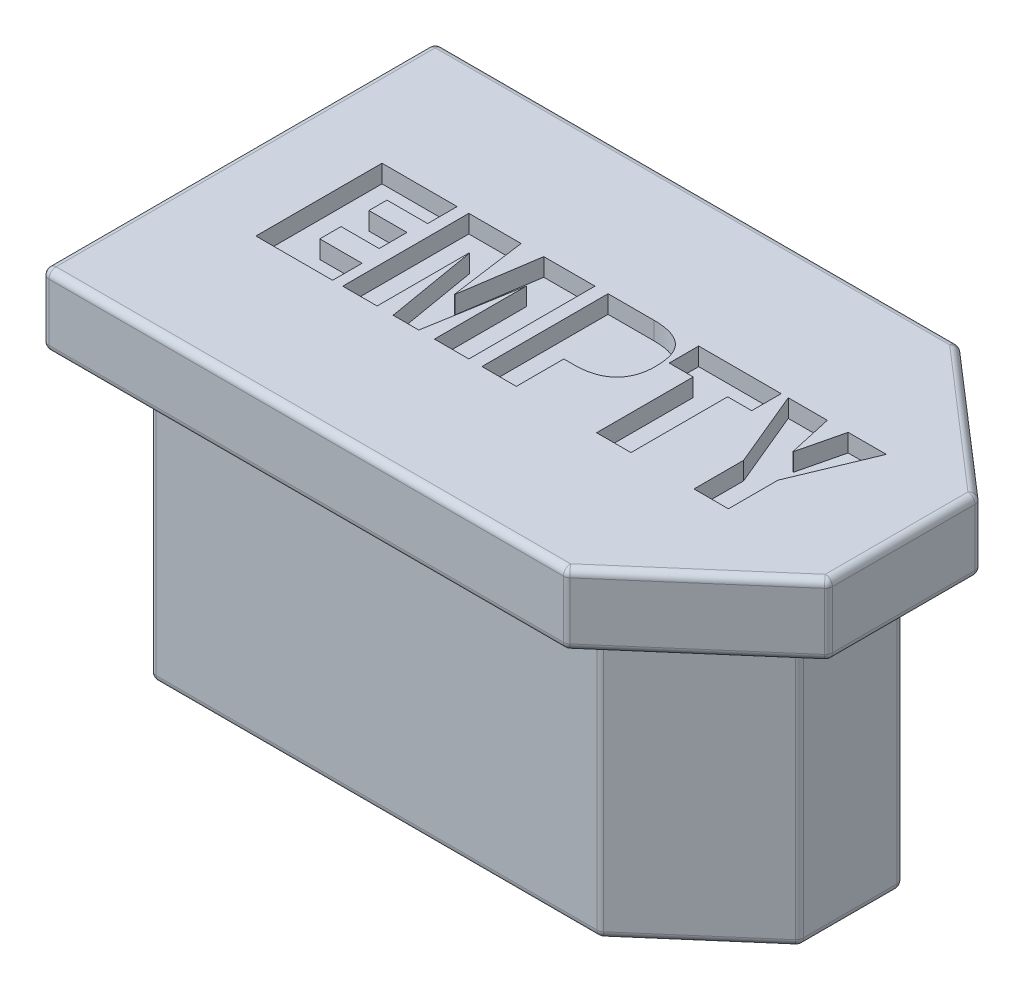
SolidWorks part; units mm, degrees
ref_plane "Front Plane" through (0, 0, 0) normal (0, 0, 1) x (1, 0, 0)
ref_plane "Top Plane" through (0, 0, 0) normal (0, 1, 0) x (1, 0, 0)
ref_plane "Right Plane" through (0, 0, 0) normal (1, 0, 0) x (0, 0, -1)
sketch "Sketch1" plane through (0, 0, 0) normal (0, 1, 0) x (1, 0, 0)
  line L0 (-7.8002, 4) -> (4.7998, 4)
  line L1 (4.7998, 4) -> (7.8002, 1.4)
  line L2 (7.8002, 1.4) -> (7.8002, -1.4)
  line L3 (7.8002, -1.4) -> (4.7998, -4)
  line L4 (4.7998, -4) -> (-7.8002, -4)
  line L5 (-7.8002, -4) -> (-7.8002, 4)
  line L6 (-7.8002, 0) -> (7.8002, 0) construction
  dimension "D1" = 8
  dimension "D2" = 12.6
  dimension "D3" = 139.09
  dimension "D4" = 2.8
extrude "Boss-Extrude1" add sketch "Sketch1" along normal mid plane 8
shell "Shell1" thickness 0.8
sketch "Sketch2" plane through (0, 4, 0) normal (0, 1, 0) x (1, 0, 0)
  line L0 (-7.8002, 4) -> (-7.8002, -4) construction
  line L1 (4.7998, 4) -> (-7.8002, 4) construction
  line L2 (7.8002, 1.4) -> (4.7998, 4) construction
  line L3 (7.8002, -1.4) -> (7.8002, 1.4) construction
  line L4 (4.7998, -4) -> (7.8002, -1.4) construction
  line L5 (-7.8002, -4) -> (4.7998, -4) construction
  line L6 (-7.8002, 4) -> (-7.8002, -4) construction
  line L7 (4.7998, 4) -> (-7.8002, 4) construction
  line L8 (7.8002, 1.4) -> (4.7998, 4) construction
  line L9 (7.8002, -1.4) -> (7.8002, 1.4) construction
  line L10 (4.7998, -4) -> (7.8002, -1.4) construction
  line L11 (-7.8002, -4) -> (4.7998, -4) construction
  line L12 (-9.3002, 5.5) -> (-9.3002, -5.5)
  line L13 (-9.3002, -5.5) -> (5.3593, -5.5)
  line L14 (5.3593, -5.5) -> (9.3002, -2.085)
  line L15 (9.3002, -2.085) -> (9.3002, 2.085)
  line L16 (9.3002, 2.085) -> (5.3593, 5.5)
  line L17 (5.3593, 5.5) -> (-9.3002, 5.5)
  dimension "D1" = 1.5
extrude "Boss-Extrude2" add sketch "Sketch2" along normal blind 2
sketch "Sketch4" plane through (0, -4, 0) normal (0, -1, 0) x (1, 0, 0)
  line L0 (-1.0002, -3.2) -> (-1.0002, -2)
  line L3 (4.5014, -3.2) -> (-7.0002, -3.2) construction
  line L5 (-1.0002, -2) -> (0.9998, -2)
  line L6 (0.9998, -2) -> (0.9998, -3.2)
  line L7 (-1.0002, -3.2) -> (0.9998, -3.2)
  dimension "D1" = 1.2
  dimension "D2" = 2
  dimension "D3" = 6
extrude "Boss-Extrude4" add sketch "Sketch4" against normal up to next
sketch "Sketch5" plane through (0, 4, 0) normal (0, -1, 0) x (1, 0, 0)
  line L0 (-0.5502, -2) -> (-0.5502, 2)
  line L1 (0.9998, -2) -> (-1.0002, -2) construction
  line L2 (-0.5502, 2) -> (0.5498, 2)
  line L3 (0.5498, 2) -> (0.5498, -2)
  line L4 (0.9998, -2) -> (-1.0002, -2) construction
  line L5 (0.5498, -2) -> (-0.5502, -2)
  line L6 (-0.0002, -2) -> (-0.0002, 2) construction
  dimension "D1" = 4
  dimension "D2" = 1.1
extrude "Cut-Extrude1" cut sketch "Sketch5" against normal blind 1
fillet "Fillet1" radius 0.2 78 edges at (4.5014, 0, -3.2) (7.0002, 0, -1.0347) (7.0002, 0, 1.0347) (4.5014, 0, 3.2) (-7.0002, 0, -3.2) (-1.0002, 0, -3.2) (-1.0002, 0, -2) (0.9998, 0, -2) (0.9998, 0, -3.2) (-7.0002, 0, 3.2) (0.9998, 4, -2.6) (0.9998, -4, -2.6) (2.7506, -4, -3.2) (-1.0002, 4, -2.6) (-1.0002, -4, -2.6) (-0.0002, 4, 2) (5.7508, -4, -2.1173) (-4.0002, -4, -3.2) (-0.0002, -4, -2) (-0.0002, 5, 2) (0.5498, 4.5, 2) (-0.5502, 4.5, 2) (0.5498, 5, 0) (-0.5502, 5, 0) (5.7508, 4, -2.1173) (2.7506, 4, -3.2) (-0.0002, 5, -2) (-4.0002, 4, -3.2) (7.0002, -4, 0) (7.0002, 4, 0) (-1.2494, -4, 3.2) (-1.2494, 4, 3.2) (5.7508, -4, 2.1173) (5.7508, 4, 2.1173) (-7.0002, -4, 0) (-7.0002, 4, 0) (-1.9705, 4, -5.5) (-9.3002, 4, 0) (-1.9705, 4, 5.5) (7.3297, 4, 3.7925) (9.3002, 4, 0) (7.3297, 4, -3.7925) (-1.9705, 6, -5.5) (-9.3002, 6, 0) (-1.9705, 6, 5.5) (7.3297, 6, 3.7925) (9.3002, 6, 0) (7.3297, 6, -3.7925) (5.3593, 5, -5.5) (9.3002, 5, -2.085) (9.3002, 5, 2.085) (5.3593, 5, 5.5) (-9.3002, 5, 5.5) (-9.3002, 5, -5.5) (-7.8002, -4, 0) (6.3, -4, 2.7) (7.8002, -4, 0) (6.3, -4, -2.7) (-1.5002, -4, -4) (-7.8002, 4, 0) (-1.5002, 4, 4) (6.3, 4, 2.7) (7.8002, 4, 0) (6.3, 4, -2.7) (-1.5002, 4, -4) (-7.8002, 0, -4) (4.7998, 0, -4) (7.8002, 0, -1.4) (7.8002, 0, 1.4) (4.7998, 0, 4) (-7.8002, 0, 4) (-1.5002, -4, 4)
sketch "Sketch6" plane through (0, 6, 0) normal (0, 1, 0) x (1, 0, 0)
  line L0 (-7.0504, 1.7632) -> (-4.9509, 1.7632)
  line L1 (-4.9509, 1.7632) -> (-4.9509, 0.9388)
  line L2 (-4.9509, 0.9388) -> (-6.0886, 0.9388)
  line L3 (-6.0886, 0.9388) -> (-6.0886, 0.4351)
  line L4 (-6.0886, 0.4351) -> (-5.0253, 0.4351)
  line L5 (-5.0253, 0.4351) -> (-5.0253, -0.3435)
  line L6 (-5.0253, -0.3435) -> (-6.0886, -0.3435)
  line L7 (-6.0886, -0.3435) -> (-6.0886, -0.9388)
  line L8 (-6.0886, -0.9388) -> (-4.9065, -0.9388)
  line L9 (-4.9065, -0.9388) -> (-4.9065, -1.7632)
  line L10 (-4.9065, -1.7632) -> (-7.0504, -1.7632)
  line L11 (-7.0504, -1.7632) -> (-7.0504, 1.7632)
  line L12 (-4.6231, 1.7632) -> (-3.1619, 1.7632)
  line L13 (-3.1619, 1.7632) -> (-2.8649, -0.3893)
  line L14 (-2.8649, -0.3893) -> (-2.8549, -0.3893)
  line L15 (-2.8549, -0.3893) -> (-2.5272, 1.7632)
  line L16 (-2.5272, 1.7632) -> (-1.0968, 1.7632)
  line L17 (-1.0968, 1.7632) -> (-1.0968, -1.7632)
  line L18 (-1.0968, -1.7632) -> (-2.0585, -1.7632)
  line L19 (-2.0585, -1.7632) -> (-2.0585, 0.8086)
  line L20 (-2.0585, 0.8086) -> (-2.4964, -1.7632)
  line L21 (-2.4964, -1.7632) -> (-3.2134, -1.7632)
  line L22 (-3.2134, -1.7632) -> (-3.6514, 0.8086)
  line L23 (-3.6514, 0.8086) -> (-3.6614, 0.8086)
  line L24 (-3.6614, 0.8086) -> (-3.6614, -1.7632)
  line L25 (-3.6614, -1.7632) -> (-4.6231, -1.7632)
  line L26 (-4.6231, -1.7632) -> (-4.6231, 1.7632)
  line L27 (-0.7304, 1.7632) -> (0.5527, 1.7632)
  line L28 (0.5333, -0.4351) -> (0.2314, -0.4351)
  line L29 (0.2314, -0.4351) -> (0.2314, -1.7632)
  line L30 (0.2314, -1.7632) -> (-0.7304, -1.7632)
  line L31 (-0.7304, 1.7632) -> (-0.7304, -1.7632)
  line L32 (-7.0504, 0) -> (7.0504, 0) construction
  line L34 (0, 0) -> (0, 1.7632) construction
  line L35 (1.8028, 1.7632) -> (4.1098, 1.7632)
  line L36 (4.1098, 1.7632) -> (4.1098, 0.9388)
  line L37 (4.1098, 0.9388) -> (3.4371, 0.9388)
  line L38 (3.4371, 0.9388) -> (3.4371, -1.7632)
  line L39 (3.4371, -1.7632) -> (2.4754, -1.7632)
  line L40 (2.4754, -1.7632) -> (2.4754, 0.9388)
  line L41 (2.4754, 0.9388) -> (1.8028, 0.9388)
  line L42 (1.8028, 0.9388) -> (1.8028, 1.7632)
  line L43 (5.982, 1.7632) -> (7.0504, 1.7632)
  line L44 (7.0504, 1.7632) -> (6.1602, -0.3757)
  line L45 (6.1602, -0.3757) -> (6.1602, -1.7632)
  line L46 (6.1602, -1.7632) -> (5.1984, -1.7632)
  line L47 (5.1984, -1.7632) -> (5.1984, -0.3757)
  line L48 (5.1984, -0.3757) -> (4.3083, 1.7632)
  line L49 (4.3083, 1.7632) -> (5.4002, 1.7632)
  line L50 (5.4002, 1.7632) -> (5.6743, 0.5317)
  line L51 (5.6743, 0.5317) -> (5.6843, 0.5317)
  line L52 (5.6843, 0.5317) -> (5.982, 1.7632)
  spline S0 degree 3 poles (0.5527, 1.7632) (0.6417, 1.7623) (0.7718, 1.7568) (0.938, 1.7296) (1.0496, 1.7008) (1.153, 1.6655) (1.2472, 1.6208) (1.3329, 1.5686) (1.4099, 1.5079) (1.4779, 1.438) (1.5361, 1.3575) (1.5858, 1.2671) (1.6265, 1.1664) (1.6578, 1.0556) (1.6878, 0.8884) (1.6959, 0.7569) (1.6954, 0.6662) knots 0 0 0 0 0.146363 0.213051 0.276109 0.335425 0.392173 0.446836 0.499792 0.552681 0.606484 0.66239 0.721576 0.784288 0.851179 1 1 1 1
  spline S1 degree 3 poles (1.6954, 0.6662) (1.6943, 0.5747) (1.6872, 0.4413) (1.6495, 0.2737) (1.6119, 0.1634) (1.5629, 0.064) (1.5077, -0.0272) (1.4415, -0.1078) (1.3677, -0.1798) (1.2857, -0.242) (1.1967, -0.2956) (1.1004, -0.3398) (0.9972, -0.3753) (0.8883, -0.4026) (0.7334, -0.4268) (0.6143, -0.4364) (0.5333, -0.4351) knots 0 0 0 0 0.150663 0.21816 0.281612 0.341727 0.399798 0.456348 0.512604 0.568801 0.625051 0.68291 0.742645 0.804042 0.867177 1 1 1 1
extrude "Cut-Extrude2" cut sketch "Sketch6" against normal blind 0.5
